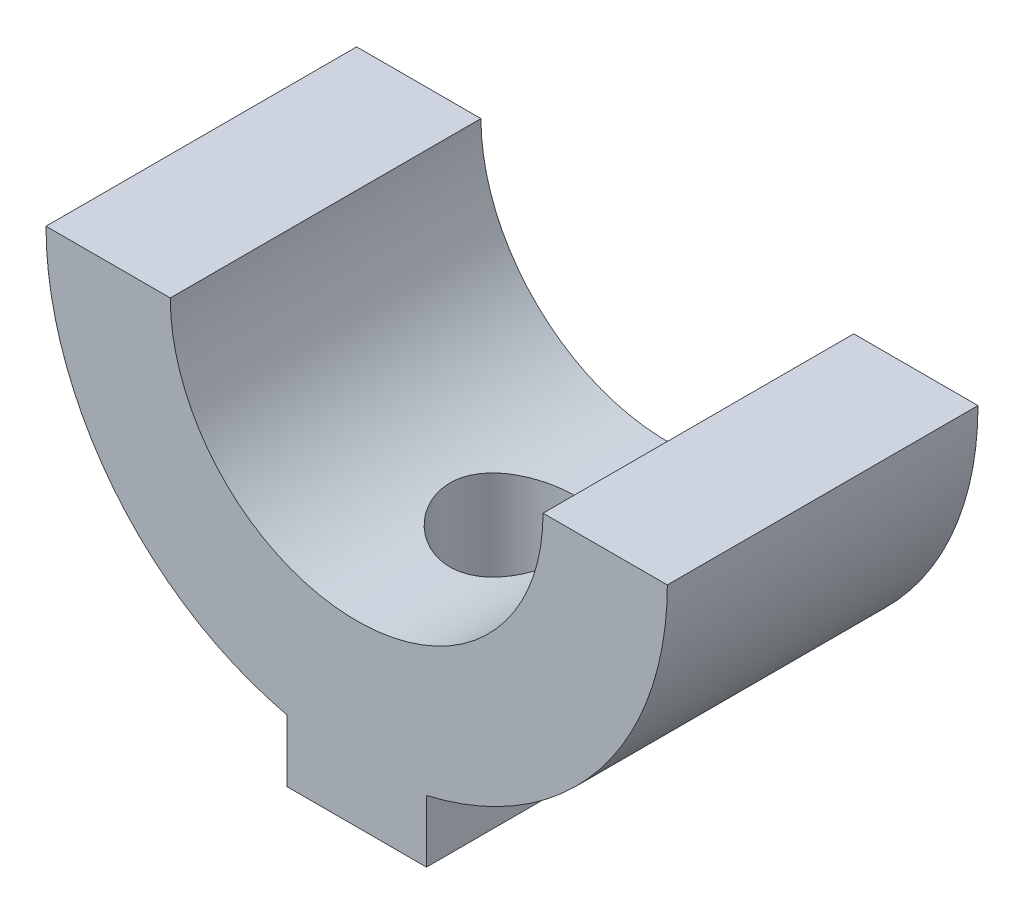
SolidWorks part; units mm, degrees
ref_plane "Front Plane" through (0, 0, 0) normal (0, 0, 1) x (1, 0, 0)
ref_plane "Top Plane" through (0, 0, 0) normal (0, 1, 0) x (1, 0, 0)
ref_plane "Right Plane" through (0, 0, 0) normal (1, 0, 0) x (0, 0, -1)
sketch "Sketch1" plane through (0, 0, 0) normal (0, 0, 1) x (1, 0, 0)
  line L0 (-236.9217, 34.6364) -> (-238.9217, 34.6364)
  line L1 (-230.9217, 34.6364) -> (-228.9217, 34.6364)
  line L2 (-233.9217, 34.6364) -> (-233.9217, 24.9555) construction
  line L3 (-232.7985, 28.7641) -> (-235.0448, 28.7641)
  line L4 (-235.0448, 28.7641) -> (-235.0448, 29.7641)
  line L5 (-232.7985, 28.7641) -> (-232.7985, 29.7641)
  arc A0 (-230.9217, 34.6364) -> (-236.9217, 34.6364) centre (-233.9217, 34.6364) cw
  arc A1 (-228.9217, 34.6364) -> (-238.9217, 34.6364) centre (-233.9217, 34.6364) cw
  arc A2 (-232.7985, 29.7641) -> (-235.0448, 29.7641) centre (-233.9217, 34.6364) cw
  point P11 (-233.9217, 28.7641)
  dimension "D1" = 3
  dimension "D4" = 5
  dimension "D2" = 2
  dimension "D3" = 2
  dimension "D5" = 1
extrude "Boss-Extrude1" add sketch "Sketch1" along normal mid plane 5 contours A0 L2 A1 L1 | L2 A0 L0 A1 A2 | A1 L2 L3 L5 | L2 A2 L4 L3
sketch "Sketch3" plane through (0, 28.7641, 0) normal (0, -1, 0) x (1, 0, 0)
  line L0 (-235.0448, 0) -> (-232.7985, 0) construction
  line L1 (-235.0448, 2.5) -> (-235.0448, -2.5) construction
  line L2 (-232.7985, 2.5) -> (-232.7985, -2.5) construction
  circle A0 centre (-233.9217, 0) radius 1
extrude "Cut-Extrude1" cut sketch "Sketch3" against normal blind 5
